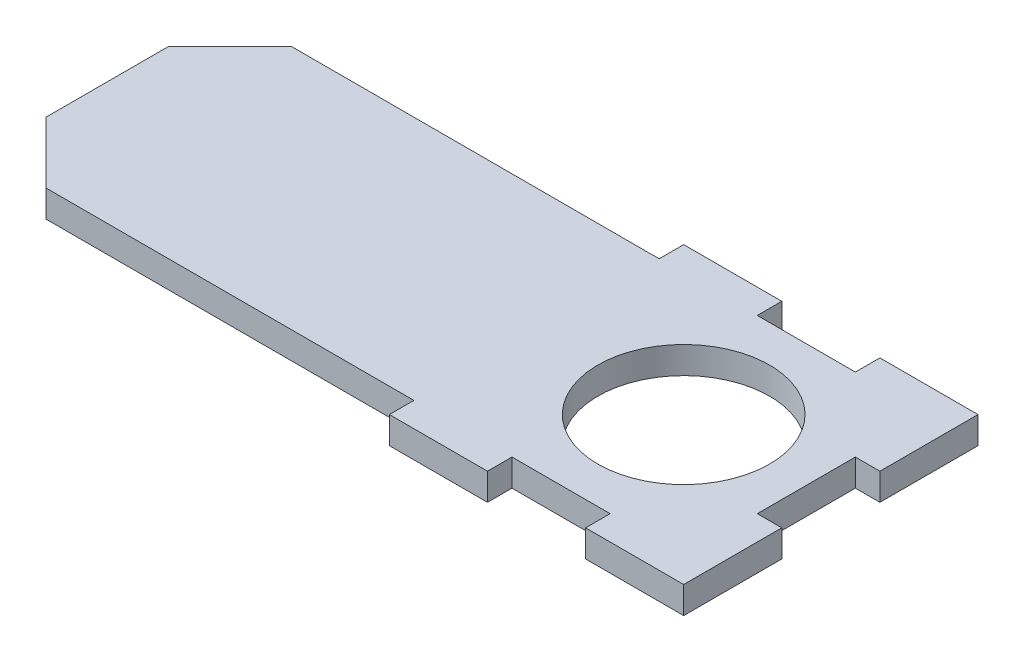
SolidWorks part; units mm, degrees
material "cardboard"
ref_plane "Front Plane" through (0, 0, 0) normal (0, 0, 1) x (1, 0, 0)
ref_plane "Top Plane" through (0, 0, 0) normal (0, 1, 0) x (1, 0, 0)
ref_plane "Right Plane" through (0, 0, 0) normal (1, 0, 0) x (0, 0, -1)
sketch "Sketch1" plane through (0, 0, 0) normal (0, 1, 0) x (1, 0, 0)
  line L0 (78.0182, 11.5977) -> (71.168, 7.6428)
  line L1 (103.5182, -12.4023) -> (110.3683, -8.4474)
  line L2 (118.668, 7.6428) -> (110.3683, 7.6428)
  line L3 (118.668, -8.4474) -> (110.3683, -8.4474)
  line L4 (71.168, 7.6428) -> (62.8683, 7.6428)
  line L5 (125.5182, 11.5977) -> (118.668, 7.6428)
  line L6 (125.5182, -12.4023) -> (118.668, -8.4474)
  line L7 (103.5182, 11.5977) -> (110.3683, 7.6428)
  line L8 (125.5182, 11.5977) -> (138.2682, 11.5977)
  line L9 (125.5182, -12.4023) -> (162.2682, -12.4023)
  line L10 (56.0182, 11.5977) -> (62.8683, 7.6428)
  line L11 (56.0182, -12.4023) -> (62.8683, -8.4474)
  line L12 (78.0182, -12.4023) -> (71.168, -8.4474)
  line L13 (71.168, -8.4474) -> (62.8683, -8.4474)
  line L14 (78.0182, 11.5977) -> (103.5182, 11.5977)
  line L15 (78.0182, -12.4023) -> (103.5182, -12.4023)
  line L16 (-11.7318, 77.3477) -> (-7.7769, 70.4976)
  line L17 (12.2682, 102.8477) -> (8.3133, 109.6979)
  line L18 (-7.7769, 117.9976) -> (-7.7769, 109.6979)
  line L19 (8.3133, 117.9976) -> (8.3133, 109.6979)
  line L20 (-7.7769, 70.4976) -> (-7.7769, 62.1979)
  line L21 (-11.7318, 124.8477) -> (-7.7769, 117.9976)
  line L22 (12.2682, 124.8477) -> (8.3133, 117.9976)
  line L23 (-11.7318, 102.8477) -> (-7.7769, 109.6979)
  line L24 (-11.7318, 124.8477) -> (-11.7318, 137.5977)
  line L25 (12.2682, 124.8477) -> (12.2682, 161.5977)
  line L26 (-11.7318, 55.3477) -> (-7.7769, 62.1979)
  line L27 (12.2682, 55.3477) -> (8.3133, 62.1979)
  line L28 (12.2682, 77.3477) -> (8.3133, 70.4976)
  line L29 (8.3133, 70.4976) -> (8.3133, 62.1979)
  line L30 (-11.7318, 77.3477) -> (-11.7318, 102.8477)
  line L31 (12.2682, 77.3477) -> (12.2682, 102.8477)
  line L32 (90.7682, 36.5977) -> (90.7682, 16.5977)
  line L33 (89.7682, 36.5977) -> (89.7682, 30.5977)
  line L34 (37.2682, 11.5977) -> (43.2682, 11.5977)
  line L35 (89.7682, 30.5977) -> (91.7682, 30.5977)
  line L36 (42.0182, 11.5977) -> (42.0182, 9.5977)
  line L37 (43.2682, 11.5977) -> (56.0182, 11.5977)
  line L38 (138.2682, 11.5977) -> (138.2682, -12.4023)
  line L39 (138.2682, 11.5977) -> (162.2682, 11.5977)
  line L40 (162.2682, 11.5977) -> (162.2682, 9.5977)
  line L41 (-28.2282, 13.952) -> (0.2682, -14.5444)
  line L42 (-28.2282, 13.952) -> (-14.0861, 28.0941)
  line L43 (0.2682, -14.5444) -> (14.4103, -0.4023)
  line L44 (-14.0861, 28.0941) -> (14.4103, -0.4023)
  line L45 (138.2682, 11.5977) -> (138.2682, 36.5977)
  line L46 (40.2682, 36.5977) -> (162.2682, 36.5977)
  line L47 (162.2682, 36.5977) -> (162.2682, 11.5977)
  line L48 (91.7682, 30.5977) -> (91.7682, 22.5977)
  line L49 (138.2682, 36.5977) -> (138.2682, 60.5977)
  line L50 (138.2682, 60.5977) -> (147.2682, 60.5977)
  line L51 (43.2682, 36.5977) -> (43.2682, 16.5977)
  line L52 (162.2682, 60.5977) -> (162.2682, 50.9197)
  line L53 (147.2682, 60.5977) -> (147.2682, 62.7977)
  line L54 (153.2682, 62.7977) -> (153.2682, 60.5977)
  line L55 (153.2682, 60.5977) -> (162.2682, 60.5977)
  line L56 (-58.7318, 137.5977) -> (-58.7318, 113.0977)
  line L57 (-38.7318, 113.0977) -> (-38.7318, 137.5977)
  line L58 (91.7682, 22.5977) -> (89.7682, 22.5977)
  line L59 (138.2682, -12.4023) -> (138.2682, -37.4023)
  line L60 (147.2682, -37.4023) -> (153.2682, -37.4023)
  line L61 (162.2682, -37.4023) -> (162.2682, -12.4023)
  line L62 (43.2682, -37.4023) -> (43.2682, -17.4023)
  line L63 (138.2682, -37.4023) -> (138.2682, -38.5823)
  line L64 (153.2682, -38.5823) -> (162.2682, -38.5823)
  line L65 (162.2682, -38.5823) -> (162.2682, -37.4023)
  line L66 (147.2682, -38.5823) -> (147.2682, -37.4023)
  line L67 (153.2682, -38.5823) -> (153.2682, -37.4023)
  line L68 (-37.9118, -138.4023) -> (-37.9118, -147.4023)
  line L69 (89.7682, 22.5977) -> (89.7682, 16.5977)
  line L70 (89.7682, 11.5977) -> (89.7682, 3.5977)
  line L71 (43.2682, -12.4023) -> (56.0182, -12.4023)
  line L72 (37.2682, -12.4023) -> (43.2682, -12.4023)
  line L73 (90.742, 11.5977) -> (90.742, -12.4023)
  line L74 (89.7682, 3.5977) -> (91.7682, 3.5977)
  line L75 (91.7682, 3.5977) -> (91.7682, -4.4023)
  line L76 (91.7682, -4.4023) -> (89.7682, -4.4023)
  line L77 (136.2682, 11.5977) -> (136.2682, 3.5977)
  line L78 (136.2682, 3.5977) -> (140.2682, 3.5977)
  line L79 (38.4482, 161.5977) -> (38.4482, 152.5977)
  line L80 (38.2682, 34.5977) -> (38.2682, 18.5977)
  line L81 (40.2682, 16.5977) -> (138.2682, 16.5977)
  line L82 (42.0182, 23.5977) -> (42.0182, 16.5977)
  line L83 (43.2682, 29.5977) -> (40.2682, 29.5977)
  line L84 (40.2682, 29.5977) -> (40.2682, 23.5977)
  line L85 (44.5182, 5.5977) -> (42.0182, 5.5977)
  line L86 (6.2682, -42.1523) -> (6.2682, -40.1523)
  line L87 (42.0182, -6.4023) -> (44.5182, -6.4023)
  line L88 (44.5182, 5.5977) -> (44.5182, -6.4023)
  line L89 (43.2682, 11.5977) -> (43.2682, 5.5977)
  line L90 (42.0182, 9.5977) -> (44.5182, 9.5977)
  line L91 (44.5182, 9.5977) -> (44.5182, 7.5977)
  line L92 (44.5182, 7.5977) -> (42.0182, 7.5977)
  line L93 (42.0182, 7.5977) -> (42.0182, 5.5977)
  line L94 (42.0182, -8.4023) -> (42.0182, -6.4023)
  line L95 (44.5182, -8.4023) -> (42.0182, -8.4023)
  line L96 (44.5182, -10.4023) -> (44.5182, -8.4023)
  line L97 (42.0182, -10.4023) -> (44.5182, -10.4023)
  line L98 (42.0182, -12.4023) -> (42.0182, -10.4023)
  line L99 (140.2682, 3.5977) -> (140.2682, -4.4023)
  line L100 (140.2682, -4.4023) -> (136.2682, -4.4023)
  line L101 (136.2682, -4.4023) -> (136.2682, -12.4023)
  line L102 (138.2682, 13.5977) -> (146.2682, 13.5977)
  line L103 (146.2682, 13.5977) -> (146.2682, 9.5977)
  line L104 (146.2682, 9.5977) -> (154.2682, 9.5977)
  line L105 (154.2682, 9.5977) -> (154.2682, 13.5977)
  line L106 (154.2682, 13.5977) -> (162.2682, 13.5977)
  line L107 (136.7682, 36.5977) -> (136.7682, 30.5977)
  line L108 (136.7682, 30.5977) -> (139.7682, 30.5977)
  line L109 (139.7682, 30.5977) -> (139.7682, 22.5977)
  line L110 (139.7682, 22.5977) -> (136.7682, 22.5977)
  line L111 (136.7682, 22.5977) -> (136.7682, 16.5977)
  line L112 (89.7682, -4.4023) -> (89.7682, -12.4023)
  line L113 (89.7682, -23.4023) -> (89.7682, -17.4023)
  line L114 (90.7682, -37.4023) -> (90.7682, -17.4023)
  line L115 (91.7682, -23.4023) -> (89.7682, -23.4023)
  line L116 (91.7682, -31.4023) -> (91.7682, -23.4023)
  line L117 (154.2682, -14.4023) -> (162.2682, -14.4023)
  line L118 (154.2682, -10.4023) -> (154.2682, -14.4023)
  line L119 (146.2682, -10.4023) -> (154.2682, -10.4023)
  line L120 (146.2682, -14.4023) -> (146.2682, -10.4023)
  line L121 (138.2682, -14.4023) -> (146.2682, -14.4023)
  line L122 (136.7682, -23.4023) -> (136.7682, -17.4023)
  line L123 (139.7682, -23.4023) -> (136.7682, -23.4023)
  line L124 (42.0182, 36.5977) -> (42.0182, 29.5977)
  line L125 (43.2682, 23.5977) -> (40.2682, 23.5977)
  line L126 (138.2682, -37.4023) -> (40.2682, -37.4023)
  line L127 (38.2682, -35.4023) -> (38.2682, -19.4023)
  line L128 (40.2682, -17.4023) -> (138.2682, -17.4023)
  line L129 (139.7682, -31.4023) -> (139.7682, -23.4023)
  line L130 (136.7682, -31.4023) -> (139.7682, -31.4023)
  line L131 (136.7682, -37.4023) -> (136.7682, -31.4023)
  line L132 (89.7682, -31.4023) -> (91.7682, -31.4023)
  line L133 (89.7682, -37.4023) -> (89.7682, -31.4023)
  line L134 (138.2682, 38.5977) -> (146.2682, 38.5977)
  line L135 (146.2682, 38.5977) -> (146.2682, 34.5977)
  line L136 (146.2682, 34.5977) -> (154.2682, 34.5977)
  line L137 (154.2682, 34.5977) -> (154.2682, 38.5977)
  line L138 (154.2682, 38.5977) -> (162.2682, 38.5977)
  line L139 (-44.2318, 133.3477) -> (-44.2318, 117.3477)
  line L140 (-55.7318, 133.3477) -> (-53.2318, 133.3477)
  line L141 (-55.7318, 133.3477) -> (-55.7318, 117.3477)
  line L142 (-55.7318, 117.3477) -> (-53.2318, 117.3477)
  line L143 (-53.2318, 133.3477) -> (-53.2318, 117.3477)
  line L144 (42.0182, -24.4023) -> (42.0182, -17.4023)
  line L145 (43.2682, -24.4023) -> (40.2682, -24.4023)
  line L146 (40.2682, -30.4023) -> (40.2682, -24.4023)
  line L147 (43.2682, -30.4023) -> (40.2682, -30.4023)
  line L148 (42.0182, -37.4023) -> (42.0182, -30.4023)
  line L149 (197.2682, 4.5977) -> (197.2682, -5.4023)
  line L150 (192.2682, 9.5977) -> (162.2682, 9.5977)
  line L151 (192.2682, -10.4023) -> (162.2682, -10.4023)
  line L152 (192.2682, 9.5977) -> (197.2682, 4.5977)
  line L153 (197.2682, -5.4023) -> (192.2682, -10.4023)
  line L154 (162.2682, -10.4023) -> (162.2682, -12.4023)
  line L155 (138.2682, 62.7977) -> (147.2682, 62.7977)
  line L156 (138.2682, 62.7977) -> (138.2682, 64.7977)
  line L157 (138.2682, 64.7977) -> (162.2682, 64.7977)
  line L158 (162.2682, 64.7977) -> (162.2682, 62.7977)
  line L159 (153.2682, 62.7977) -> (162.2682, 62.7977)
  line L160 (-41.7318, 117.3477) -> (-44.2318, 117.3477)
  line L161 (-41.7318, 133.3477) -> (-41.7318, 117.3477)
  line L162 (-41.7318, 133.3477) -> (-44.2318, 133.3477)
  line L163 (155.6682, 50.9197) -> (162.2682, 50.9197)
  line L164 (155.6682, 50.9197) -> (155.6682, 46.4197)
  line L165 (155.6682, 46.4197) -> (162.2682, 46.4197)
  line L166 (162.2682, 46.4197) -> (162.2682, 36.5977)
  line L167 (12.2682, -78.1523) -> (8.3133, -71.3021)
  line L168 (-11.7318, -103.6523) -> (-7.7769, -110.5024)
  line L169 (8.3133, -118.8021) -> (8.3133, -110.5024)
  line L170 (12.2682, -37.4023) -> (12.2682, -43.4023)
  line L171 (12.2682, -42.1523) -> (10.2682, -42.1523)
  line L172 (12.2682, -43.4023) -> (12.2682, -56.1523)
  line L173 (-7.7769, -118.8021) -> (-7.7769, -110.5024)
  line L174 (8.3133, -71.3021) -> (8.3133, -63.0024)
  line L175 (12.2682, -125.6523) -> (8.3133, -118.8021)
  line L176 (-11.7318, -125.6523) -> (-7.7769, -118.8021)
  line L177 (12.2682, -103.6523) -> (8.3133, -110.5024)
  line L178 (12.2682, -125.6523) -> (12.2682, -138.4023)
  line L179 (-11.7318, -125.6523) -> (-11.7318, -162.4023)
  line L180 (12.2682, -56.1523) -> (8.3133, -63.0024)
  line L181 (-11.7318, -56.1523) -> (-7.7769, -63.0024)
  line L182 (37.2682, -43.4023) -> (17.2682, -43.4023)
  line L183 (-11.7318, -78.1523) -> (-7.7769, -71.3021)
  line L184 (-7.7769, -71.3021) -> (-7.7769, -63.0024)
  line L185 (12.2682, -78.1523) -> (12.2682, -103.6523)
  line L186 (-11.7318, -78.1523) -> (-11.7318, -103.6523)
  line L187 (37.2682, -90.9023) -> (17.2682, -90.9023)
  line L188 (37.2682, -89.9023) -> (31.2682, -89.9023)
  line L189 (31.2682, -89.9023) -> (31.2682, -91.9023)
  line L190 (12.2682, -138.4023) -> (-11.7318, -138.4023)
  line L191 (12.2682, -138.4023) -> (12.2682, -162.4023)
  line L192 (12.2682, -162.4023) -> (10.2682, -162.4023)
  line L193 (12.2682, -138.4023) -> (37.2682, -138.4023)
  line L194 (37.2682, -40.4023) -> (37.2682, -162.4023)
  line L195 (-36.7318, -43.4023) -> (-16.7318, -43.4023)
  line L196 (37.2682, -162.4023) -> (12.2682, -162.4023)
  line L197 (31.2682, -91.9023) -> (23.2682, -91.9023)
  line L198 (37.2682, -138.4023) -> (61.2682, -138.4023)
  line L199 (61.2682, -138.4023) -> (61.2682, -147.4023)
  line L200 (61.2682, -162.4023) -> (51.5902, -162.4023)
  line L201 (61.2682, -147.4023) -> (63.4682, -147.4023)
  line L202 (63.4682, -153.4023) -> (61.2682, -153.4023)
  line L203 (61.2682, -153.4023) -> (61.2682, -162.4023)
  line L204 (-11.7318, -43.4023) -> (-11.7318, -56.1523)
  line L205 (-11.7318, -37.4023) -> (-11.7318, -43.4023)
  line L206 (23.2682, -91.9023) -> (23.2682, -89.9023)
  line L207 (-11.7318, -138.4023) -> (-36.7318, -138.4023)
  line L208 (-36.7318, -147.4023) -> (-36.7318, -153.4023)
  line L209 (38.4482, 146.5977) -> (38.4482, 137.5977)
  line L210 (35.2682, -38.4023) -> (19.2682, -38.4023)
  line L211 (17.2682, -40.4023) -> (17.2682, -138.4023)
  line L212 (24.2682, -42.1523) -> (17.2682, -42.1523)
  line L213 (30.2682, -43.4023) -> (30.2682, -40.4023)
  line L214 (30.2682, -40.4023) -> (24.2682, -40.4023)
  line L215 (6.2682, -44.6523) -> (6.2682, -42.1523)
  line L216 (-36.7318, -162.4023) -> (-11.7318, -162.4023)
  line L217 (-5.7318, -42.1523) -> (-5.7318, -44.6523)
  line L218 (6.2682, -44.6523) -> (-5.7318, -44.6523)
  line L219 (12.2682, -43.4023) -> (6.2682, -43.4023)
  line L220 (10.2682, -42.1523) -> (10.2682, -44.6523)
  line L221 (10.2682, -44.6523) -> (8.2682, -44.6523)
  line L222 (8.2682, -44.6523) -> (8.2682, -42.1523)
  line L223 (8.2682, -42.1523) -> (6.2682, -42.1523)
  line L224 (-7.7318, -42.1523) -> (-5.7318, -42.1523)
  line L225 (-7.7318, -44.6523) -> (-7.7318, -42.1523)
  line L226 (-9.7318, -44.6523) -> (-7.7318, -44.6523)
  line L227 (-9.7318, -42.1523) -> (-9.7318, -44.6523)
  line L228 (-11.7318, -42.1523) -> (-9.7318, -42.1523)
  line L229 (-36.7318, -138.4023) -> (-37.9118, -138.4023)
  line L230 (-37.9118, -153.4023) -> (-37.9118, -162.4023)
  line L231 (-37.9118, -162.4023) -> (-36.7318, -162.4023)
  line L232 (-37.9118, -147.4023) -> (-36.7318, -147.4023)
  line L233 (-37.9118, -153.4023) -> (-36.7318, -153.4023)
  line L234 (-161.7318, 37.7777) -> (-152.7318, 37.7777)
  line L235 (23.2682, -89.9023) -> (17.2682, -89.9023)
  line L236 (12.2682, -89.9023) -> (4.2682, -89.9023)
  line L237 (12.2682, -90.8761) -> (-11.7318, -90.8761)
  line L238 (4.2682, -89.9023) -> (4.2682, -91.9023)
  line L239 (4.2682, -91.9023) -> (-3.7318, -91.9023)
  line L240 (-3.7318, -91.9023) -> (-3.7318, -89.9023)
  line L241 (12.2682, -136.4023) -> (4.2682, -136.4023)
  line L242 (4.2682, -136.4023) -> (4.2682, -140.4023)
  line L243 (4.2682, -140.4023) -> (-3.7318, -140.4023)
  line L244 (-3.7318, -140.4023) -> (-3.7318, -136.4023)
  line L245 (-3.7318, -136.4023) -> (-11.7318, -136.4023)
  line L246 (14.2682, -138.4023) -> (14.2682, -146.4023)
  line L247 (14.2682, -146.4023) -> (10.2682, -146.4023)
  line L248 (10.2682, -146.4023) -> (10.2682, -154.4023)
  line L249 (10.2682, -154.4023) -> (14.2682, -154.4023)
  line L250 (14.2682, -154.4023) -> (14.2682, -162.4023)
  line L251 (37.2682, -136.9023) -> (31.2682, -136.9023)
  line L252 (31.2682, -136.9023) -> (31.2682, -139.9023)
  line L253 (31.2682, -139.9023) -> (23.2682, -139.9023)
  line L254 (37.2682, -42.1523) -> (30.2682, -42.1523)
  line L255 (24.2682, -43.4023) -> (24.2682, -40.4023)
  line L256 (-36.7318, -138.4023) -> (-36.7318, -40.4023)
  line L257 (-34.7318, -38.4023) -> (-18.7318, -38.4023)
  line L258 (-16.7318, -40.4023) -> (-16.7318, -138.4023)
  line L259 (23.2682, -139.9023) -> (23.2682, -136.9023)
  line L260 (23.2682, -136.9023) -> (17.2682, -136.9023)
  line L261 (-3.7318, -89.9023) -> (-11.7318, -89.9023)
  line L262 (-22.7318, -89.9023) -> (-16.7318, -89.9023)
  line L263 (-36.7318, -90.9023) -> (-16.7318, -90.9023)
  line L264 (-22.7318, -91.9023) -> (-22.7318, -89.9023)
  line L265 (-30.7318, -91.9023) -> (-22.7318, -91.9023)
  line L266 (-13.7318, -154.4023) -> (-13.7318, -162.4023)
  line L267 (-9.7318, -154.4023) -> (-13.7318, -154.4023)
  line L268 (-9.7318, -146.4023) -> (-9.7318, -154.4023)
  line L269 (-13.7318, -146.4023) -> (-9.7318, -146.4023)
  line L270 (-13.7318, -138.4023) -> (-13.7318, -146.4023)
  line L271 (-22.7318, -136.9023) -> (-16.7318, -136.9023)
  line L272 (-22.7318, -139.9023) -> (-22.7318, -136.9023)
  line L273 (-30.7318, -139.9023) -> (-22.7318, -139.9023)
  line L274 (-23.7318, -42.1523) -> (-16.7318, -42.1523)
  line L275 (-23.7318, -43.4023) -> (-23.7318, -40.4023)
  line L276 (-29.7318, -40.4023) -> (-23.7318, -40.4023)
  line L277 (-29.7318, -43.4023) -> (-29.7318, -40.4023)
  line L278 (-36.7318, -42.1523) -> (-29.7318, -42.1523)
  line L279 (-30.7318, -136.9023) -> (-30.7318, -139.9023)
  line L280 (-36.7318, -136.9023) -> (-30.7318, -136.9023)
  line L281 (-30.7318, -89.9023) -> (-30.7318, -91.9023)
  line L282 (-36.7318, -89.9023) -> (-30.7318, -89.9023)
  line L283 (39.2682, -138.4023) -> (39.2682, -146.4023)
  line L284 (39.2682, -146.4023) -> (35.2682, -146.4023)
  line L285 (35.2682, -146.4023) -> (35.2682, -154.4023)
  line L286 (35.2682, -154.4023) -> (39.2682, -154.4023)
  line L287 (39.2682, -154.4023) -> (39.2682, -162.4023)
  line L288 (5.2682, -197.4023) -> (-4.7318, -197.4023)
  line L289 (10.2682, -192.4023) -> (10.2682, -162.4023)
  line L290 (-9.7318, -192.4023) -> (-9.7318, -162.4023)
  line L291 (10.2682, -192.4023) -> (5.2682, -197.4023)
  line L292 (-4.7318, -197.4023) -> (-9.7318, -192.4023)
  line L293 (-9.7318, -162.4023) -> (-11.7318, -162.4023)
  line L294 (63.4682, -138.4023) -> (63.4682, -147.4023)
  line L295 (63.4682, -138.4023) -> (65.4682, -138.4023)
  line L296 (65.4682, -138.4023) -> (65.4682, -162.4023)
  line L297 (65.4682, -162.4023) -> (63.4682, -162.4023)
  line L298 (63.4682, -153.4023) -> (63.4682, -162.4023)
  line L299 (-36.7318, -12.4023) -> (-42.7318, -12.4023)
  line L300 (-41.4818, -12.4023) -> (-41.4818, -10.4023)
  line L301 (-42.7318, -12.4023) -> (-55.4818, -12.4023)
  line L302 (51.5902, -155.8023) -> (51.5902, -162.4023)
  line L303 (51.5902, -155.8023) -> (47.0902, -155.8023)
  line L304 (-42.7318, -37.4023) -> (-42.7318, -17.4023)
  line L305 (47.0902, -155.8023) -> (47.0902, -162.4023)
  line L306 (47.0902, -162.4023) -> (37.2682, -162.4023)
  line L307 (-77.4818, -12.4023) -> (-70.6317, -8.4474)
  line L308 (-102.9818, 11.5977) -> (-109.832, 7.6428)
  line L309 (-118.1317, -8.4474) -> (-109.832, -8.4474)
  line L310 (-118.1317, 7.6428) -> (-109.832, 7.6428)
  line L311 (-70.6317, -8.4474) -> (-62.332, -8.4474)
  line L312 (-124.9818, -12.4023) -> (-118.1317, -8.4474)
  line L313 (-124.9818, 11.5977) -> (-118.1317, 7.6428)
  line L314 (-102.9818, -12.4023) -> (-109.832, -8.4474)
  line L315 (-124.9818, -12.4023) -> (-137.7318, -12.4023)
  line L316 (-42.7318, 36.5977) -> (-42.7318, 16.5977)
  line L317 (-124.9818, 11.5977) -> (-161.7318, 11.5977)
  line L318 (-55.4818, -12.4023) -> (-62.332, -8.4474)
  line L319 (-55.4818, 11.5977) -> (-62.332, 7.6428)
  line L320 (-77.4818, 11.5977) -> (-70.6317, 7.6428)
  line L321 (-70.6317, 7.6428) -> (-62.332, 7.6428)
  line L322 (-77.4818, -12.4023) -> (-102.9818, -12.4023)
  line L323 (-77.4818, 11.5977) -> (-102.9818, 11.5977)
  line L324 (-90.2318, -37.4023) -> (-90.2318, -17.4023)
  line L325 (-42.7318, 11.5977) -> (-55.4818, 11.5977)
  line L326 (-36.7318, 11.5977) -> (-42.7318, 11.5977)
  line L327 (-89.2318, -37.4023) -> (-89.2318, -31.4023)
  line L328 (-89.2318, -31.4023) -> (-91.2318, -31.4023)
  line L329 (-137.7318, -12.4023) -> (-137.7318, 11.5977)
  line L330 (-137.7318, -12.4023) -> (-161.7318, -12.4023)
  line L331 (-161.7318, -12.4023) -> (-161.7318, -10.4023)
  line L332 (-137.7318, -12.4023) -> (-137.7318, -37.4023)
  line L333 (138.2682, -38.5823) -> (147.2682, -38.5823)
  line L334 (-37.7318, -35.4023) -> (-37.7318, -19.4023)
  line L335 (-39.7318, -17.4023) -> (-137.7318, -17.4023)
  line L336 (-41.4818, -24.4023) -> (-41.4818, -17.4023)
  line L337 (-42.7318, -30.4023) -> (-39.7318, -30.4023)
  line L338 (-39.7318, -30.4023) -> (-39.7318, -24.4023)
  line L339 (-43.9818, -6.4023) -> (-41.4818, -6.4023)
  line L340 (-39.7318, -37.4023) -> (-161.7318, -37.4023)
  line L341 (-41.4818, 5.5977) -> (-43.9818, 5.5977)
  line L342 (-43.9818, -6.4023) -> (-43.9818, 5.5977)
  line L343 (-42.7318, -12.4023) -> (-42.7318, -6.4023)
  line L344 (-41.4818, -10.4023) -> (-43.9818, -10.4023)
  line L345 (-43.9818, -10.4023) -> (-43.9818, -8.4023)
  line L346 (-43.9818, -8.4023) -> (-41.4818, -8.4023)
  line L347 (-41.4818, -8.4023) -> (-41.4818, -6.4023)
  line L348 (-41.4818, 7.5977) -> (-41.4818, 5.5977)
  line L349 (-43.9818, 7.5977) -> (-41.4818, 7.5977)
  line L350 (-43.9818, 9.5977) -> (-43.9818, 7.5977)
  line L351 (-41.4818, 9.5977) -> (-43.9818, 9.5977)
  line L352 (-41.4818, 11.5977) -> (-41.4818, 9.5977)
  line L353 (-161.7318, -37.4023) -> (-161.7318, -12.4023)
  line L354 (-91.2318, -31.4023) -> (-91.2318, -23.4023)
  line L355 (-137.7318, -37.4023) -> (-137.7318, -61.4023)
  line L356 (-137.7318, -61.4023) -> (-146.7318, -61.4023)
  line L357 (-161.7318, -61.4023) -> (-161.7318, -51.7243)
  line L358 (-146.7318, -61.4023) -> (-146.7318, -63.6023)
  line L359 (-152.7318, -63.6023) -> (-152.7318, -61.4023)
  line L360 (-152.7318, -61.4023) -> (-161.7318, -61.4023)
  line L361 (-91.2318, -23.4023) -> (-89.2318, -23.4023)
  line L362 (-137.7318, 11.5977) -> (-137.7318, 36.5977)
  line L363 (-146.7318, 36.5977) -> (-152.7318, 36.5977)
  line L364 (-161.7318, 36.5977) -> (-161.7318, 11.5977)
  line L365 (-137.7318, 36.5977) -> (-137.7318, 37.7777)
  line L366 (-161.7318, 37.7777) -> (-161.7318, 36.5977)
  line L367 (-146.7318, 37.7777) -> (-146.7318, 36.5977)
  line L368 (-152.7318, 37.7777) -> (-152.7318, 36.5977)
  line L369 (-146.7318, 37.7777) -> (-137.7318, 37.7777)
  line L370 (-89.2318, -23.4023) -> (-89.2318, -17.4023)
  line L371 (-89.2318, -12.4023) -> (-89.2318, -4.4023)
  line L372 (-90.2056, -12.4023) -> (-90.2056, 11.5977)
  line L373 (-89.2318, -4.4023) -> (-91.2318, -4.4023)
  line L374 (-41.4818, -37.4023) -> (-41.4818, -30.4023)
  line L375 (-42.7318, -24.4023) -> (-39.7318, -24.4023)
  line L376 (-137.7318, 36.5977) -> (-39.7318, 36.5977)
  line L377 (-37.7318, 34.5977) -> (-37.7318, 18.5977)
  line L378 (-39.7318, 16.5977) -> (-137.7318, 16.5977)
  line L379 (-91.2318, -4.4023) -> (-91.2318, 3.5977)
  line L380 (-91.2318, 3.5977) -> (-89.2318, 3.5977)
  line L381 (-135.7318, -12.4023) -> (-135.7318, -4.4023)
  line L382 (-135.7318, -4.4023) -> (-139.7318, -4.4023)
  line L383 (-139.7318, -4.4023) -> (-139.7318, 3.5977)
  line L384 (-139.7318, 3.5977) -> (-135.7318, 3.5977)
  line L385 (-135.7318, 3.5977) -> (-135.7318, 11.5977)
  line L386 (-137.7318, -14.4023) -> (-145.7318, -14.4023)
  line L387 (-145.7318, -14.4023) -> (-145.7318, -10.4023)
  line L388 (-145.7318, -10.4023) -> (-153.7318, -10.4023)
  line L389 (-153.7318, -10.4023) -> (-153.7318, -14.4023)
  line L390 (-153.7318, -14.4023) -> (-161.7318, -14.4023)
  line L391 (-136.2318, -37.4023) -> (-136.2318, -31.4023)
  line L392 (-36.7318, 90.0977) -> (-16.7318, 90.0977)
  line L393 (-36.7318, 89.0977) -> (-30.7318, 89.0977)
  line L394 (-41.4818, 23.5977) -> (-41.4818, 16.5977)
  line L395 (-42.7318, 23.5977) -> (-39.7318, 23.5977)
  line L396 (-39.7318, 29.5977) -> (-39.7318, 23.5977)
  line L397 (-42.7318, 29.5977) -> (-39.7318, 29.5977)
  line L398 (-41.4818, 36.5977) -> (-41.4818, 29.5977)
  line L399 (-136.2318, -31.4023) -> (-139.2318, -31.4023)
  line L400 (-139.2318, -31.4023) -> (-139.2318, -23.4023)
  line L401 (-139.2318, -23.4023) -> (-136.2318, -23.4023)
  line L402 (-136.2318, -23.4023) -> (-136.2318, -17.4023)
  line L403 (-89.2318, 3.5977) -> (-89.2318, 11.5977)
  line L404 (-89.2318, 22.5977) -> (-89.2318, 16.5977)
  line L405 (-90.2318, 36.5977) -> (-90.2318, 16.5977)
  line L406 (-91.2318, 22.5977) -> (-89.2318, 22.5977)
  line L407 (-91.2318, 30.5977) -> (-91.2318, 22.5977)
  line L408 (-153.7318, 13.5977) -> (-161.7318, 13.5977)
  line L409 (-153.7318, 9.5977) -> (-153.7318, 13.5977)
  line L410 (-145.7318, 9.5977) -> (-153.7318, 9.5977)
  line L411 (-145.7318, 13.5977) -> (-145.7318, 9.5977)
  line L412 (-137.7318, 13.5977) -> (-145.7318, 13.5977)
  line L413 (-136.2318, 22.5977) -> (-136.2318, 16.5977)
  line L414 (-139.2318, 22.5977) -> (-136.2318, 22.5977)
  line L415 (-139.2318, 30.5977) -> (-139.2318, 22.5977)
  line L416 (-136.2318, 30.5977) -> (-139.2318, 30.5977)
  line L417 (-136.2318, 36.5977) -> (-136.2318, 30.5977)
  line L418 (-89.2318, 30.5977) -> (-91.2318, 30.5977)
  line L419 (-89.2318, 36.5977) -> (-89.2318, 30.5977)
  line L420 (-137.7318, -39.4023) -> (-145.7318, -39.4023)
  line L421 (-145.7318, -39.4023) -> (-145.7318, -35.4023)
  line L422 (-145.7318, -35.4023) -> (-153.7318, -35.4023)
  line L423 (-153.7318, -35.4023) -> (-153.7318, -39.4023)
  line L424 (-153.7318, -39.4023) -> (-161.7318, -39.4023)
  line L425 (-11.7318, 41.3477) -> (-9.7318, 41.3477)
  line L426 (-30.7318, 89.0977) -> (-30.7318, 91.0977)
  line L427 (-11.7318, 137.5977) -> (12.2682, 137.5977)
  line L428 (-11.7318, 137.5977) -> (-11.7318, 161.5977)
  line L429 (-11.7318, 161.5977) -> (-9.7318, 161.5977)
  line L430 (-11.7318, 137.5977) -> (-36.7318, 137.5977)
  line L431 (-36.7318, 137.5977) -> (-36.7318, 161.5977)
  line L432 (-36.7318, 161.5977) -> (-11.7318, 161.5977)
  line L433 (-36.7318, 137.5977) -> (-36.7318, 42.5977)
  line L434 (-36.7318, 42.5977) -> (-16.7318, 42.5977)
  line L435 (-16.7318, 42.5977) -> (-16.7318, 137.5977)
  line L436 (-30.7318, 91.0977) -> (-22.7318, 91.0977)
  line L437 (-36.7318, 137.5977) -> (-60.7318, 137.5977)
  line L438 (-60.7318, 137.5977) -> (-60.7318, 146.5977)
  line L439 (-60.7318, 161.5977) -> (-51.0538, 161.5977)
  line L440 (-60.7318, 146.5977) -> (-62.9318, 146.5977)
  line L441 (-62.9318, 152.5977) -> (-60.7318, 152.5977)
  line L442 (-60.7318, 152.5977) -> (-60.7318, 161.5977)
  line L443 (-58.7318, 113.0977) -> (-38.7318, 113.0977)
  line L444 (37.2682, 42.5977) -> (17.2682, 42.5977)
  line L445 (-22.7318, 91.0977) -> (-22.7318, 89.0977)
  line L446 (37.2682, 137.5977) -> (37.2682, 42.5977)
  line L447 (17.2682, 42.5977) -> (17.2682, 137.5977)
  line L448 (12.2682, 137.5977) -> (37.2682, 137.5977)
  line L449 (37.2682, 146.5977) -> (37.2682, 152.5977)
  line L450 (37.2682, 161.5977) -> (12.2682, 161.5977)
  line L451 (12.2682, 36.5977) -> (12.2682, 55.3477)
  line L452 (37.2682, 137.5977) -> (38.4482, 137.5977)
  line L453 (38.4482, 161.5977) -> (37.2682, 161.5977)
  line L454 (38.4482, 146.5977) -> (37.2682, 146.5977)
  line L455 (38.4482, 152.5977) -> (37.2682, 152.5977)
  line L456 (-36.7318, 42.5977) -> (-36.7318, 39.5977)
  line L457 (-34.7318, 37.5977) -> (-18.7318, 37.5977)
  line L458 (-16.7318, 39.5977) -> (-16.7318, 42.5977)
  line L459 (35.2682, 37.5977) -> (19.2682, 37.5977)
  line L460 (17.2682, 39.5977) -> (17.2682, 42.5977)
  line L461 (-5.7318, 43.8477) -> (-5.7318, 41.3477)
  line L462 (-22.7318, 89.0977) -> (-16.7318, 89.0977)
  line L463 (6.2682, 41.3477) -> (6.2682, 43.8477)
  line L464 (-5.7318, 43.8477) -> (6.2682, 43.8477)
  line L465 (-11.7318, 42.5977) -> (-5.7318, 42.5977)
  line L466 (-9.7318, 41.3477) -> (-9.7318, 43.8477)
  line L467 (-9.7318, 43.8477) -> (-7.7318, 43.8477)
  line L468 (-7.7318, 43.8477) -> (-7.7318, 41.3477)
  line L469 (-7.7318, 41.3477) -> (-5.7318, 41.3477)
  line L470 (8.2682, 41.3477) -> (6.2682, 41.3477)
  line L471 (8.2682, 43.8477) -> (8.2682, 41.3477)
  line L472 (10.2682, 43.8477) -> (8.2682, 43.8477)
  line L473 (10.2682, 41.3477) -> (10.2682, 43.8477)
  line L474 (12.2682, 41.3477) -> (10.2682, 41.3477)
  line L475 (-11.7318, 89.0977) -> (-3.7318, 89.0977)
  line L476 (-11.7318, 90.0715) -> (12.2682, 90.0715)
  line L477 (-3.7318, 89.0977) -> (-3.7318, 91.0977)
  line L478 (-3.7318, 91.0977) -> (4.2682, 91.0977)
  line L479 (4.2682, 91.0977) -> (4.2682, 89.0977)
  line L480 (-11.7318, 135.5977) -> (-3.7318, 135.5977)
  line L481 (-3.7318, 135.5977) -> (-3.7318, 139.5977)
  line L482 (-3.7318, 139.5977) -> (4.2682, 139.5977)
  line L483 (4.2682, 139.5977) -> (4.2682, 135.5977)
  line L484 (4.2682, 135.5977) -> (12.2682, 135.5977)
  line L485 (-13.7318, 137.5977) -> (-13.7318, 145.5977)
  line L486 (-13.7318, 145.5977) -> (-9.7318, 145.5977)
  line L487 (-9.7318, 145.5977) -> (-9.7318, 153.5977)
  line L488 (-9.7318, 153.5977) -> (-13.7318, 153.5977)
  line L489 (-13.7318, 153.5977) -> (-13.7318, 161.5977)
  line L490 (-36.7318, 136.0977) -> (-30.7318, 136.0977)
  line L491 (-30.7318, 136.0977) -> (-30.7318, 139.0977)
  line L492 (-30.7318, 139.0977) -> (-22.7318, 139.0977)
  line L493 (-22.7318, 139.0977) -> (-22.7318, 136.0977)
  line L494 (-22.7318, 136.0977) -> (-16.7318, 136.0977)
  line L495 (4.2682, 89.0977) -> (12.2682, 89.0977)
  line L496 (23.2682, 89.0977) -> (17.2682, 89.0977)
  line L497 (37.2682, 90.0977) -> (17.2682, 90.0977)
  line L498 (23.2682, 91.0977) -> (23.2682, 89.0977)
  line L499 (31.2682, 91.0977) -> (23.2682, 91.0977)
  line L500 (-36.7318, 41.3477) -> (-29.7318, 41.3477)
  line L501 (30.2682, 39.5977) -> (24.2682, 39.5977)
  line L502 (24.2682, 41.3477) -> (17.2682, 41.3477)
  line L503 (-29.7318, 42.5977) -> (-29.7318, 39.5977)
  line L504 (-23.7318, 41.3477) -> (-16.7318, 41.3477)
  line L505 (14.2682, 153.5977) -> (14.2682, 161.5977)
  line L506 (10.2682, 153.5977) -> (14.2682, 153.5977)
  line L507 (10.2682, 145.5977) -> (10.2682, 153.5977)
  line L508 (14.2682, 145.5977) -> (10.2682, 145.5977)
  line L509 (14.2682, 137.5977) -> (14.2682, 145.5977)
  line L510 (23.2682, 136.0977) -> (17.2682, 136.0977)
  line L511 (23.2682, 139.0977) -> (23.2682, 136.0977)
  line L512 (31.2682, 139.0977) -> (23.2682, 139.0977)
  line L513 (31.2682, 136.0977) -> (31.2682, 139.0977)
  line L514 (37.2682, 136.0977) -> (31.2682, 136.0977)
  line L515 (31.2682, 89.0977) -> (31.2682, 91.0977)
  line L516 (37.2682, 89.0977) -> (31.2682, 89.0977)
  line L517 (12.2682, 36.5977) -> (21.2327, 27.6332)
  line L518 (37.2682, -12.4023) -> (28.3037, -21.3668)
  line L519 (-11.7318, -37.4023) -> (-20.6963, -28.4378)
  line L520 (24.2682, 42.5977) -> (24.2682, 39.5977)
  line L521 (-23.7318, 42.5977) -> (-23.7318, 39.5977)
  line L522 (30.2682, 42.5977) -> (30.2682, 39.5977)
  line L523 (37.2682, 41.3477) -> (30.2682, 41.3477)
  line L524 (-38.7318, 137.5977) -> (-38.7318, 145.5977)
  line L525 (-38.7318, 145.5977) -> (-34.7318, 145.5977)
  line L526 (-34.7318, 145.5977) -> (-34.7318, 153.5977)
  line L527 (-34.7318, 153.5977) -> (-38.7318, 153.5977)
  line L528 (-38.7318, 153.5977) -> (-38.7318, 161.5977)
  line L529 (-58.7318, 136.0977) -> (-51.7318, 136.0977)
  line L530 (-51.7318, 136.0977) -> (-51.7318, 139.0977)
  line L531 (-51.7318, 139.0977) -> (-45.7318, 139.0977)
  line L532 (-45.7318, 139.0977) -> (-45.7318, 136.0977)
  line L533 (-45.7318, 136.0977) -> (-38.7318, 136.0977)
  line L534 (-11.7318, 36.5977) -> (-11.7318, 55.3477)
  line L535 (43.2682, -6.4023) -> (43.2682, -12.4023)
  line L536 (6.2682, 42.5977) -> (12.2682, 42.5977)
  line L537 (-42.7318, 5.5977) -> (-42.7318, 11.5977)
  line L538 (-5.7318, -43.4023) -> (-11.7318, -43.4023)
  line L539 (-4.7318, 196.5977) -> (5.2682, 196.5977)
  line L540 (-9.7318, 191.5977) -> (-9.7318, 161.5977)
  line L541 (10.2682, 191.5977) -> (10.2682, 161.5977)
  line L542 (-9.7318, 191.5977) -> (-4.7318, 196.5977)
  line L543 (5.2682, 196.5977) -> (10.2682, 191.5977)
  line L544 (134.0182, 55.5977) -> (118.0182, 55.5977)
  line L545 (134.0182, 55.5977) -> (134.0182, 53.0977)
  line L546 (-196.7318, -5.4023) -> (-196.7318, 4.5977)
  line L547 (-191.7318, -10.4023) -> (-161.7318, -10.4023)
  line L548 (-191.7318, 9.5977) -> (-161.7318, 9.5977)
  line L549 (-191.7318, -10.4023) -> (-196.7318, -5.4023)
  line L550 (-196.7318, 4.5977) -> (-191.7318, 9.5977)
  line L551 (-161.7318, 9.5977) -> (-161.7318, 11.5977)
  line L552 (-137.7318, -63.6023) -> (-146.7318, -63.6023)
  line L553 (-137.7318, -63.6023) -> (-137.7318, -65.6023)
  line L554 (-137.7318, -65.6023) -> (-161.7318, -65.6023)
  line L555 (-161.7318, -65.6023) -> (-161.7318, -63.6023)
  line L556 (10.2682, 161.5977) -> (12.2682, 161.5977)
  line L557 (-152.7318, -63.6023) -> (-161.7318, -63.6023)
  line L558 (134.0182, 53.0977) -> (118.0182, 53.0977)
  line L559 (118.0182, 55.5977) -> (118.0182, 53.0977)
  line L560 (134.0182, 44.0977) -> (118.0182, 44.0977)
  line L561 (134.0182, 41.5977) -> (134.0182, 44.0977)
  line L562 (134.0182, 41.5977) -> (118.0182, 41.5977)
  line L563 (118.0182, 41.5977) -> (118.0182, 44.0977)
  line L564 (136.7682, 58.5977) -> (136.7682, 51.5977)
  line L565 (136.7682, 51.5977) -> (139.7682, 51.5977)
  line L566 (-155.1318, -51.7243) -> (-161.7318, -51.7243)
  line L567 (-155.1318, -51.7243) -> (-155.1318, -47.2243)
  line L568 (-155.1318, -47.2243) -> (-161.7318, -47.2243)
  line L569 (-62.9318, 137.5977) -> (-62.9318, 146.5977)
  line L570 (-62.9318, 137.5977) -> (-64.9318, 137.5977)
  line L571 (-64.9318, 137.5977) -> (-64.9318, 161.5977)
  line L572 (-64.9318, 161.5977) -> (-62.9318, 161.5977)
  line L573 (-62.9318, 152.5977) -> (-62.9318, 161.5977)
  line L574 (-161.7318, -47.2243) -> (-161.7318, -37.4023)
  line L575 (139.7682, 51.5977) -> (139.7682, 45.5977)
  line L576 (-46.0939, 123.4425) -> (-47.2318, 123.4425)
  line L577 (-51.3697, 127.4838) -> (-50.2318, 127.4838)
  line L578 (-51.3697, 127.4838) -> (-51.3697, 123.4425)
  line L579 (-51.3697, 123.4425) -> (-50.2318, 123.4425)
  line L580 (-50.2318, 127.4838) -> (-50.2318, 123.4425)
  line L581 (-47.2318, 127.4838) -> (-47.2318, 123.4425)
  line L582 (-46.0939, 127.4838) -> (-47.2318, 127.4838)
  line L583 (-46.0939, 127.4838) -> (-46.0939, 123.4425)
  line L584 (139.7682, 45.5977) -> (136.7682, 45.5977)
  line L585 (136.7682, 45.5977) -> (136.7682, 38.5977)
  line L586 (113.7682, 38.5977) -> (138.2682, 38.5977)
  line L587 (113.7682, 58.5977) -> (113.7682, 38.5977)
  line L588 (138.2682, 58.5977) -> (113.7682, 58.5977)
  line L589 (56.2682, -134.1523) -> (56.2682, -118.1523)
  line L590 (56.2682, -134.1523) -> (53.7682, -134.1523)
  line L591 (-51.0538, 154.9977) -> (-51.0538, 161.5977)
  line L592 (-51.0538, 154.9977) -> (-46.5538, 154.9977)
  line L593 (-46.5538, 154.9977) -> (-46.5538, 161.5977)
  line L594 (-46.5538, 161.5977) -> (-36.7318, 161.5977)
  line L595 (53.7682, -134.1523) -> (53.7682, -118.1523)
  line L596 (56.2682, -118.1523) -> (53.7682, -118.1523)
  line L597 (-13.6252, 34.7043) -> (-11.7318, 36.5977)
  line L598 (-20.6963, 34.7043) -> (-22.8176, 36.8256)
  line L599 (-34.8384, 20.5622) -> (-36.9597, 22.6835)
  line L600 (-36.9597, 22.6835) -> (-22.8176, 36.8256)
  line L601 (6.2682, -40.1523) -> (-5.7318, -40.1523)
  line L602 (42.0182, 5.5977) -> (40.0182, 5.5977)
  line L603 (-5.7318, -42.1523) -> (-5.7318, -40.1523)
  line L604 (42.0182, -6.4023) -> (40.0182, -6.4023)
  line L605 (40.0182, 5.5977) -> (40.0182, -6.4023)
  line L606 (-41.4818, -6.4023) -> (-39.4818, -6.4023)
  line L607 (-39.4818, -6.4023) -> (-39.4818, 5.5977)
  line L608 (-41.4818, 5.5977) -> (-39.4818, 5.5977)
  line L609 (-5.7318, 41.3477) -> (-5.7318, 39.3477)
  line L610 (-5.7318, 39.3477) -> (6.2682, 39.3477)
  line L611 (6.2682, 41.3477) -> (6.2682, 39.3477)
  line L612 (-36.7318, 11.5977) -> (-34.8384, 13.4911)
  line L613 (-29.7318, 39.5977) -> (-23.7318, 39.5977)
  line L614 (26.1824, -19.2454) -> (19.1113, -26.3165)
  line L615 (19.1113, 25.5119) -> (26.1824, 18.4409)
  line L616 (26.1824, 18.4409) -> (28.3037, 20.5622)
  line L617 (44.7682, -134.1523) -> (44.7682, -118.1523)
  line L618 (42.2682, -134.1523) -> (44.7682, -134.1523)
  line L619 (42.2682, -134.1523) -> (42.2682, -118.1523)
  line L620 (42.2682, -118.1523) -> (44.7682, -118.1523)
  line L621 (59.2682, -136.9023) -> (52.2682, -136.9023)
  line L622 (52.2682, -136.9023) -> (52.2682, -139.9023)
  line L623 (52.2682, -139.9023) -> (46.2682, -139.9023)
  line L624 (46.2682, -139.9023) -> (46.2682, -136.9023)
  line L625 (46.2682, -136.9023) -> (39.2682, -136.9023)
  line L626 (39.2682, -113.9023) -> (39.2682, -138.4023)
  line L627 (59.2682, -113.9023) -> (39.2682, -113.9023)
  line L628 (59.2682, -138.4023) -> (59.2682, -113.9023)
  line L629 (-133.4818, -56.4023) -> (-117.4818, -56.4023)
  line L630 (-133.4818, -56.4023) -> (-133.4818, -53.9023)
  line L631 (-133.4818, -53.9023) -> (-117.4818, -53.9023)
  line L632 (-117.4818, -56.4023) -> (-117.4818, -53.9023)
  line L633 (-133.4818, -44.9023) -> (-117.4818, -44.9023)
  line L634 (-133.4818, -42.4023) -> (-133.4818, -44.9023)
  line L635 (-133.4818, -42.4023) -> (-117.4818, -42.4023)
  line L636 (-117.4818, -42.4023) -> (-117.4818, -44.9023)
  line L637 (-136.2318, -59.4023) -> (-136.2318, -52.4023)
  line L638 (-136.2318, -52.4023) -> (-139.2318, -52.4023)
  line L639 (-139.2318, -52.4023) -> (-139.2318, -46.4023)
  line L640 (-139.2318, -46.4023) -> (-136.2318, -46.4023)
  line L641 (-136.2318, -46.4023) -> (-136.2318, -39.4023)
  line L642 (-113.2318, -39.4023) -> (-137.7318, -39.4023)
  line L643 (-113.2318, -59.4023) -> (-113.2318, -39.4023)
  line L644 (-137.7318, -59.4023) -> (-113.2318, -59.4023)
  line L645 (128.1543, 51.2356) -> (124.113, 51.2356)
  line L646 (128.1543, 51.2356) -> (128.1543, 50.0977)
  line L647 (128.1543, 50.0977) -> (124.113, 50.0977)
  line L648 (124.113, 51.2356) -> (124.113, 50.0977)
  line L649 (128.1543, 47.0977) -> (124.113, 47.0977)
  line L650 (19.1113, 25.5119) -> (21.2327, 27.6332)
  line L651 (128.1543, 45.9598) -> (128.1543, 47.0977)
  line L652 (128.1543, 45.9598) -> (124.113, 45.9598)
  line L653 (124.113, 45.9598) -> (124.113, 47.0977)
  line L654 (51.9061, -128.2884) -> (51.9061, -124.2471)
  line L655 (51.9061, -128.2884) -> (50.7682, -128.2884)
  line L656 (50.7682, -128.2884) -> (50.7682, -124.2471)
  line L657 (51.9061, -124.2471) -> (50.7682, -124.2471)
  line L658 (47.7682, -128.2884) -> (47.7682, -124.2471)
  line L659 (46.6303, -128.2884) -> (47.7682, -128.2884)
  line L660 (46.6303, -128.2884) -> (46.6303, -124.2471)
  line L661 (46.6303, -124.2471) -> (47.7682, -124.2471)
  line L662 (-127.6179, -52.0402) -> (-123.5766, -52.0402)
  line L663 (-127.6179, -52.0402) -> (-127.6179, -50.9023)
  line L664 (-127.6179, -50.9023) -> (-123.5766, -50.9023)
  line L665 (-123.5766, -52.0402) -> (-123.5766, -50.9023)
  line L666 (-127.6179, -47.9023) -> (-123.5766, -47.9023)
  line L667 (-127.6179, -46.7644) -> (-127.6179, -47.9023)
  line L668 (-127.6179, -46.7644) -> (-123.5766, -46.7644)
  line L669 (-123.5766, -46.7644) -> (-123.5766, -47.9023)
  line L670 (28.3037, 20.5622) -> (37.2682, 11.5977)
  line L671 (19.1113, -26.3165) -> (21.2327, -28.4378)
  line L672 (26.1824, -19.2454) -> (28.3037, -21.3668)
  line L673 (-18.575, -26.3165) -> (-25.646, -19.2454)
  line L674 (-25.646, -19.2454) -> (-27.7673, -21.3668)
  line L675 (-18.575, -26.3165) -> (-20.6963, -28.4378)
  line L676 (21.2327, -28.4378) -> (12.2682, -37.4023)
  line L677 (-27.7673, -21.3668) -> (-36.7318, -12.4023)
  line L678 (37.2682, 42.5977) -> (37.2682, 39.5977)
  circle A0 centre (156.9857, 41.8802) radius 1.5
  circle A1 centre (143.5507, 55.3152) radius 1.5
  circle A2 centre (155.925, 54.2546) radius 1.5
  circle A3 centre (144.6113, 42.9409) radius 1.5
  circle A4 centre (150.2682, 48.5977) radius 3.1
  circle A5 centre (150.2682, 24.0977) radius 5
  circle A6 centre (150.2682, -24.9023) radius 5
  circle A7 centre (67.0182, 26.5977) radius 5
  circle A8 centre (114.2688, 26.5977) radius 5
  circle A9 centre (67.0182, -27.4023) radius 5
  circle A10 centre (114.2688, -27.4023) radius 5
  circle A11 centre (150.2682, -0.4023) radius 7
  circle A12 centre (42.5507, -157.1198) radius 1.5
  circle A13 centre (55.9857, -143.6848) radius 1.5
  circle A14 centre (54.925, -156.0591) radius 1.5
  circle A15 centre (43.6113, -144.7454) radius 1.5
  circle A16 centre (49.2682, -150.4023) radius 3.1
  circle A17 centre (24.7682, -150.4023) radius 5
  circle A18 centre (-42.0143, 156.3152) radius 1.5
  circle A19 centre (-55.4493, 142.8802) radius 1.5
  circle A20 centre (-54.3887, 155.2546) radius 1.5
  circle A21 centre (-43.075, 143.9409) radius 1.5
  circle A22 centre (-48.7318, 149.5977) radius 3.1
  circle A23 centre (-24.2318, -150.4023) radius 5
  circle A24 centre (27.2682, -67.1523) radius 5
  circle A25 centre (27.2682, -114.4029) radius 5
  circle A26 centre (-26.7318, -67.1523) radius 5
  circle A27 centre (-26.7318, -114.4029) radius 5
  circle A28 centre (0.2682, -150.4023) radius 7
  circle A29 centre (-156.4493, -42.6848) radius 1.5
  circle A30 centre (-24.2318, 149.5977) radius 5
  circle A31 centre (24.7682, 149.5977) radius 5
  circle A32 centre (-143.0143, -56.1198) radius 1.5
  circle A33 centre (-155.3887, -55.0591) radius 1.5
  circle A34 centre (-144.075, -43.7454) radius 1.5
  circle A35 centre (-149.7318, -49.4023) radius 3.1
  circle A36 centre (-149.7318, -24.9023) radius 5
  circle A37 centre (-149.7318, 24.0977) radius 5
  circle A38 centre (-66.4818, -27.4023) radius 5
  circle A39 centre (-113.7324, -27.4023) radius 5
  circle A40 centre (-66.4818, 26.5977) radius 5
  circle A41 centre (-113.7324, 26.5977) radius 5
  circle A42 centre (-149.7318, -0.4023) radius 7
  circle A43 centre (-26.7318, 66.3477) radius 5
  circle A44 centre (-26.7318, 113.5983) radius 5
  circle A45 centre (27.2682, 66.3477) radius 5
  circle A46 centre (27.2682, 113.5983) radius 5
  arc A47 (40.2682, 36.5977) -> (38.2682, 34.5977) centre (40.2682, 34.5977) ccw
  arc A48 (38.2682, 18.5977) -> (40.2682, 16.5977) centre (40.2682, 18.5977) ccw
  arc A49 (-18.7318, 37.5977) -> (-16.7318, 39.5977) centre (-18.7318, 39.5977) ccw
  arc A50 (-36.7318, 39.5977) -> (-34.7318, 37.5977) centre (-34.7318, 39.5977) ccw
  arc A51 (37.2682, 39.5977) -> (35.2682, 37.5977) centre (35.2682, 39.5977) cw
  arc A52 (19.2682, 37.5977) -> (17.2682, 39.5977) centre (19.2682, 39.5977) cw
  arc A53 (40.2682, -37.4023) -> (38.2682, -35.4023) centre (40.2682, -35.4023) cw
  arc A54 (38.2682, -19.4023) -> (40.2682, -17.4023) centre (40.2682, -19.4023) cw
  arc A55 (37.2682, -40.4023) -> (35.2682, -38.4023) centre (35.2682, -40.4023) ccw
  arc A56 (19.2682, -38.4023) -> (17.2682, -40.4023) centre (19.2682, -40.4023) ccw
  arc A57 (-36.7318, -40.4023) -> (-34.7318, -38.4023) centre (-34.7318, -40.4023) cw
  arc A58 (-18.7318, -38.4023) -> (-16.7318, -40.4023) centre (-18.7318, -40.4023) cw
  arc A59 (-39.7318, -37.4023) -> (-37.7318, -35.4023) centre (-39.7318, -35.4023) ccw
  arc A60 (-37.7318, -19.4023) -> (-39.7318, -17.4023) centre (-39.7318, -19.4023) ccw
  arc A61 (-39.7318, 36.5977) -> (-37.7318, 34.5977) centre (-39.7318, 34.5977) cw
  arc A62 (-37.7318, 18.5977) -> (-39.7318, 16.5977) centre (-39.7318, 18.5977) cw
  arc A63 (-13.6252, 34.7043) -> (-20.6963, 34.7043) centre (-17.1607, 38.2398) cw
  arc A64 (-34.8384, 20.5622) -> (-34.8384, 13.4911) centre (-38.3739, 17.0266) cw
  circle A65 centre (0.2682, 149.5977) radius 7
  point P194 (0.2682, -0.4023)
  point P589 (0.2682, -0.4023)
  point P595 (0.2682, -0.4023)
  point P596 (0.2682, -0.4023)
  point P601 (0.2682, -0.4023)
  point P604 (0.2682, -0.4023)
  point P629 (0.2682, -0.4023)
  point P660 (0.2682, -0.4023)
  point P686 (0.2682, -0.4023)
  point P715 (0.2682, -0.4023)
  point P716 (0.2682, -0.4023)
  point P740 (0.2682, -0.4023)
  point P743 (0.2682, -0.4023)
  point P783 (0.2682, -0.4023)
  point P809 (0.2682, -0.4023)
  point P816 (0.2682, -0.4023)
  point P829 (0.2682, -0.4023)
  point P860 (0.2682, -0.4023)
  point P885 (0.2682, -0.4023)
  point P890 (0.2682, -0.4023)
  point P910 (0.2682, -0.4023)
extrude "Boss-Extrude1" add sketch "Sketch1" along normal blind 2.2 contours L551 L548 L550 L546 L549 L547 L331 L330 L389 L388 L387 L329 L382 L383 L384 L317 L411 L410 L409 A42
